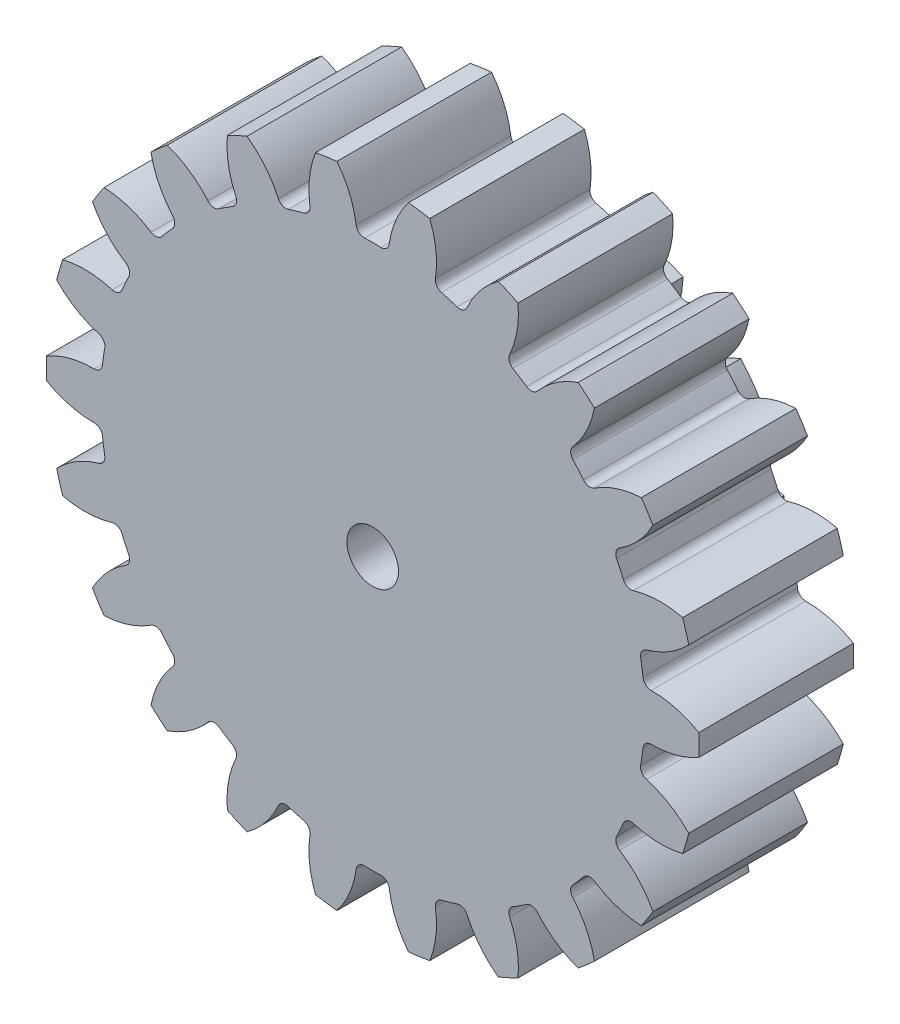
SolidWorks part; units mm, degrees
ref_plane "Front" through (0, 0, 0) normal (0, 0, 1) x (1, 0, 0)
ref_plane "Top" through (0, 0, 0) normal (0, 1, 0) x (1, 0, 0)
ref_plane "Right" through (0, 0, 0) normal (1, 0, 0) x (0, 0, -1)
sketch "Sketch1" plane through (0, 0, 0) normal (0, 0, 1) x (1, 0, 0)
  circle A0 centre (0, 0) radius 6.6667
  circle A1 centre (0, 0) radius 10
  circle A2 centre (0, 0) radius 8.3333
  dimension "D1" = 20
  dimension "D2" = 13.3333
  dimension "D3" = 16.6667
extrude "Boss-Extrude1" add sketch "Sketch1" along normal mid plane 5 contours A1
sketch "Sketch3" plane through (0, 0, 0) normal (0, 0, 1) x (1, 0, 0)
  line L0 (0, 0) -> (0, 10) construction
  line L1 (-1.3036, 8.2307) -> (1.3036, 8.2307) construction
  line L2 (-2.2285, 10.7719) -> (0, 4.6491) construction
  line L3 (0, 0) -> (3.0902, 9.5106) construction
  line L4 (1.3036, 8.2307) -> (3.7833, 7.4251) construction
  line L5 (0, 0) -> (-0.9018, 6.6054) construction
  circle A0 centre (0, 0) radius 10 construction
  arc A1 (-2.7219, 10.6579) -> (-0.9018, 6.6054) centre (-8.6908, 5.542) cw
  arc A2 (2.7219, 10.6579) -> (0.9018, 6.6054) centre (8.6908, 5.542) ccw
  arc A3 (0.9018, 6.6054) -> (-0.9018, 6.6054) centre (0, 0) ccw
  circle A4 centre (0, 0) radius 6.6667 construction
  circle A6 centre (0, 0) radius 8.3333 construction
  circle A7 centre (0, 0) radius 11
  arc A8 (2.7219, 10.6579) -> (-2.7219, 10.6579) centre (0, 0) ccw
  circle A9 centre (0, 0) radius 10 construction
  dimension "D3" = 18
  dimension "D2" = 20
extrude "Cut-Extrude1" cut sketch "Sketch3" against normal through all both and the other way through all
fillet "Fillet2" radius 0.5 2 edges at (0.9018, 6.6054, 0) (-0.9018, 6.6054, 0)
pattern_circular "CirPattern1" count 10 over 360 about axis through (0, 0, 0) along (0, 0, 1) of "Cut-Extrude1", "Fillet2"
sketch "Sketch4" plane through (0, 0, 2.5) normal (0, 0, 1) x (1, 0, 0)
  circle A0 centre (0, 0) radius 17.4167
  circle A1 centre (0, 0) radius 19
  circle A2 centre (0, 0) radius 15.8333
  dimension "D1" = 34.8333
  dimension "D2" = 38
  dimension "D3" = 31.6667
extrude "Boss-Extrude2" add sketch "Sketch4" along normal blind 9 separate body
sketch "Sketch5" plane through (0, 0, 11.5) normal (0, 0, 1) x (1, 0, 0)
  line L0 (0, 0) -> (0, 19) construction
  line L1 (-1.2425, 17.3723) -> (1.2425, 17.3723) construction
  line L2 (-0.9193, 15.8066) -> (0, 0) construction
  line L3 (-2.1565, 19.8834) -> (0, 13.9586) construction
  line L4 (0, 0) -> (2.704, 18.8066) construction
  line L5 (1.2425, 17.3723) -> (3.7022, 17.0186) construction
  circle A0 centre (0, 0) radius 19 construction
  arc A1 (-2.9634, 19.7792) -> (-0.9193, 15.8066) centre (-6.4237, 15.4865) cw
  arc A2 (2.9634, 19.7792) -> (0.9193, 15.8066) centre (6.4237, 15.4865) ccw
  circle A3 centre (0, 0) radius 15.8333 construction
  arc A4 (0.9193, 15.8066) -> (-0.9193, 15.8066) centre (0, 0) ccw
  circle A6 centre (0, 0) radius 17.4167 construction
  circle A7 centre (0, 0) radius 20
  arc A8 (2.9634, 19.7792) -> (-2.9634, 19.7792) centre (0, 0) ccw
  circle A9 centre (0, 0) radius 19 construction
  dimension "D2" = 20
  dimension "D3" = 8.182
extrude "Cut-Extrude2" cut sketch "Sketch5" against normal up to surface (9 mm away) up to face at (19, 0, 2.5)
fillet "Fillet3" radius 0.475 2 edges at (0.9193, 15.8066, 7) (-0.9193, 15.8066, 7)
pattern_circular "CirPattern2" count 22 over 360 about axis through (0, 0, 0) along (0, 0, 1) of "Cut-Extrude2", "Fillet3"
sketch "Sketch6" plane through (0, 0, 11.5) normal (0, 0, 1) x (1, 0, 0)
  circle A0 centre (0, 0) radius 1.5
  dimension "D1" = 3
extrude "Cut-Extrude3" cut sketch "Sketch6" against normal through all
equation "\"bot_n\"= 10'bottom number of teeth"
equation "\"bot_m\"= \"bot_od\" / ( \"bot_n\" + 2 )'bottom module"
equation "\"bot_p\"= \"bot_m\" * pi'bottom pitch"
equation "\"bot_d\"= \"bot_m\" * \"bot_n\"'bottom primitive diameter"
equation "\"bot_da\"= \"bot_d\" + 2 * \"bot_m\"'bottom head diamater"
equation "\"bot_df\"= \"bot_d\" - 2 * \"bot_m\"'bottom foot diameter"
equation "\"bot_od\"= 20'bottom outer diameter"
equation "\"D1@Sketch1\"=\"bot_od\""
equation "\"D2@Sketch1\"=\"bot_df\""
equation "\"D3@Sketch1\"=\"bot_d\""
equation "\"D3@Sketch3\"= 180 / \"bot_n\""
equation "\"D1@Fillet2\"=.3*\"bot_m\""
equation "\"top_n\"= 22'top number of teeth"
equation "\"top_od\"= 38'top outer diameter"
equation "\"top_m\"= \"top_od\" / ( \"top_n\" + 2 )'top module"
equation "\"top_p\"= \"top_m\" * pi'top pitch"
equation "\"top_d\"= \"top_m\" * \"top_n\"'top primitive diameter"
equation "\"top_da\"= \"top_d\" + 2 * \"top_m\"'top head diameter"
equation "\"top_df\"= \"top_d\" - 2 * \"top_m\"'top foot diamter"
equation "\"D1@CirPattern1\"= \"bot_n\""
equation "\"D1@Sketch4\"= \"top_m\" * \"top_n\""
equation "\"D2@Sketch4\"= (\"top_n\" + 2) * \"top_m\""
equation "\"D3@Sketch4\"=\"top_df\""
equation "\"D3@Sketch5\"= 180 / \"top_n\""
equation "\"D1@Fillet3\"=.3 * \"top_m\""
equation "\"D1@CirPattern2\"= \"top_n\""
